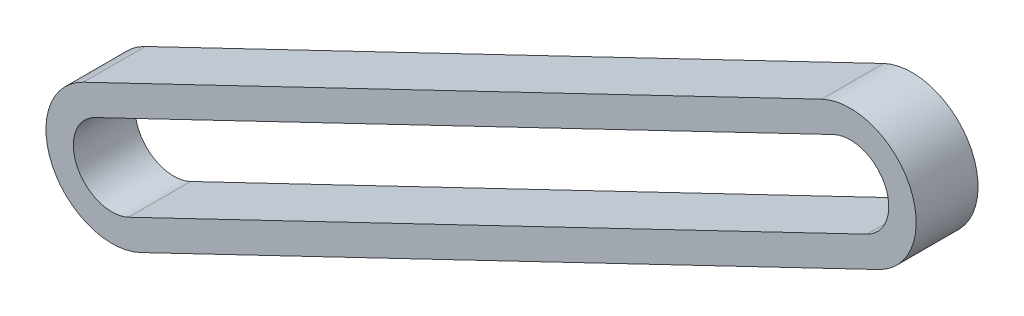
SolidWorks part; units mm, degrees
material "Rubber"
ref_plane "Front Plane" through (0, 0, 0) normal (0, 0, 1) x (1, 0, 0)
ref_plane "Top Plane" through (0, 0, 0) normal (0, 1, 0) x (1, 0, 0)
ref_plane "Right Plane" through (0, 0, 0) normal (1, 0, 0) x (0, 0, -1)
sketch "Sketch1" plane through (0, 0, 0) normal (0, 0, 1) x (1, 0, 0)
  line L0 (0, 0) -> (35.8, 17.1867) construction
  line L1 (-1.3849, 2.8848) -> (34.4151, 20.0715)
  line L2 (1.3849, -2.8848) -> (37.1849, 14.3019)
  line L3 (0, 0) -> (35.8, 17.1867) construction
  line L4 (-0.8102, 1.6876) -> (34.9898, 18.8743)
  line L5 (0.8102, -1.6876) -> (36.6102, 15.4991)
  arc A0 (-1.3849, 2.8848) -> (1.3849, -2.8848) centre (0, 0) ccw
  arc A1 (37.1849, 14.3019) -> (34.4151, 20.0715) centre (35.8, 17.1867) ccw
  arc A2 (-0.8102, 1.6876) -> (0.8102, -1.6876) centre (0, 0) ccw
  arc A3 (36.6102, 15.4991) -> (34.9898, 18.8743) centre (35.8, 17.1867) ccw
  circle A4 centre (0, 0) radius 1.872 construction
  circle A5 centre (0, 0) radius 3.2 construction
  point P4 (17.9, 8.5934)
  point P9 (17.9, 8.5934)
extrude "Boss-Extrude1" add sketch "Sketch1" against normal blind 3 contours A2 L5 A3 L4
